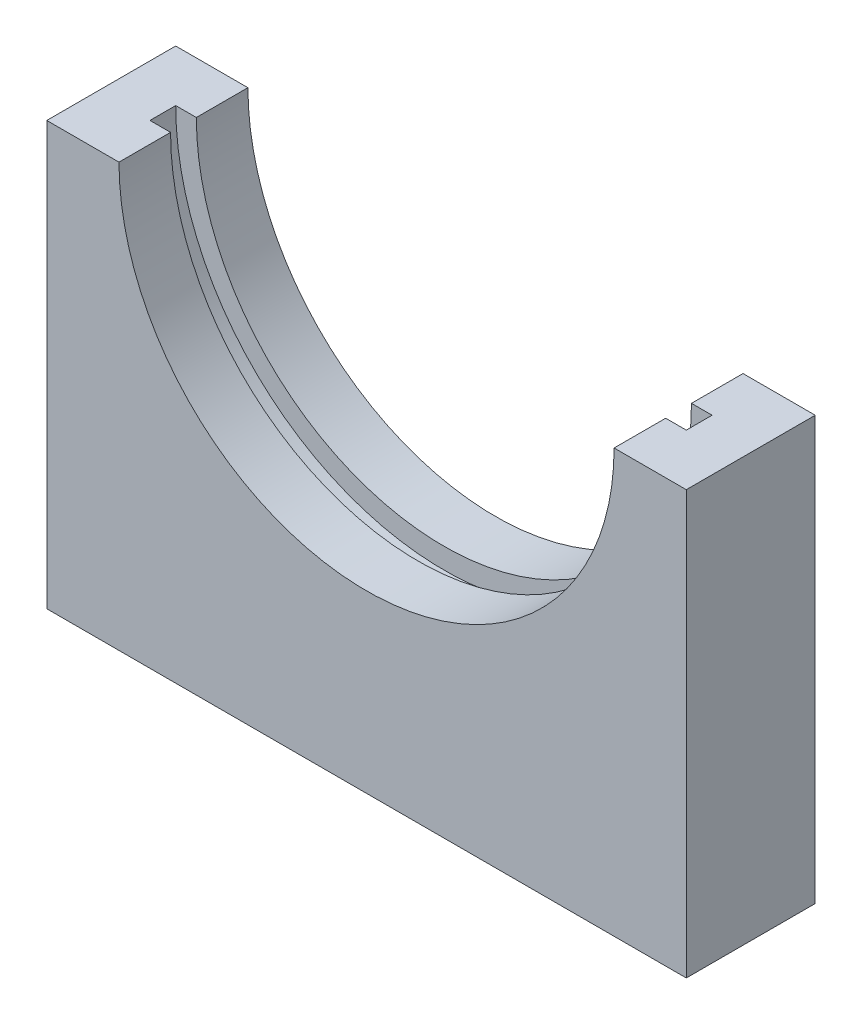
SolidWorks part; units mm, degrees
ref_plane "Front Plane" through (0, 0, 0) normal (0, 0, 1) x (1, 0, 0)
ref_plane "Top Plane" through (0, 0, 0) normal (0, 1, 0) x (1, 0, 0)
ref_plane "Right Plane" through (0, 0, 0) normal (1, 0, 0) x (0, 0, -1)
sketch "Sketch1" plane through (0, 0, 0) normal (0, 0, 1) x (1, 0, 0)
  line L0 (-26, 0) -> (-31, 0)
  line L1 (26, 0) -> (31, 0)
  line L2 (-31, 0) -> (-31, -41)
  line L3 (-31, -41) -> (-31, -23.434)
  line L4 (31, 0) -> (31, -41)
  line L5 (-31, -41) -> (31, -41)
  arc A0 (-26, 0) -> (26, 0) centre (0, 0) ccw
extrude "Boss-Extrude2" add sketch "Sketch1" along normal blind 2.5 contours A0 L0 L2 L5 L4 L1
sketch "Sketch2" plane through (0, 0, 2.5) normal (0, 0, 1) x (1, 0, 0)
  line L0 (-24, 0) -> (-31, 0)
  line L1 (-31, 0) -> (-31, -41)
  line L2 (-31, -41) -> (31, -41)
  line L3 (-31, -41) -> (31, -41) construction
  line L4 (31, 0) -> (31, -41) construction
  line L5 (31, -41) -> (31, 0)
  line L6 (31, 0) -> (24, 0)
  arc A0 (-24, 0) -> (24, 0) centre (0, 0) ccw
extrude "Boss-Extrude3" add sketch "Sketch2" along normal blind 5
sketch "Sketch3" plane through (0, 0, 0) normal (0, 0, -1) x (-1, 0, 0)
  line L0 (-24, 0) -> (-31, 0)
  line L1 (-31, 0) -> (-31, -41)
  line L2 (-31, -41) -> (31, -41)
  line L3 (31, -41) -> (31, 0)
  line L4 (24, 0) -> (31, 0)
  arc A0 (-24, 0) -> (24, 0) centre (0, 0) ccw
extrude "Boss-Extrude4" add sketch "Sketch3" along normal blind 5
sketch "Sketch4" plane through (0, -41, 0) normal (0, -1, 0) x (-1, 0, 0)
  line L0 (24, -7.5) -> (31, -7.5) construction
  line L3 (31, -7.5) -> (-31, -7.5) construction
  line L4 (31, -7.5) -> (31, 5) construction
  circle A0 centre (0, -1.25) radius 2.75
  point P0 (27.5, -7.5)
  point P5 (0, -1.25)
  dimension "D1" = 6.25
  dimension "D2" = 31
extrude "Cut-Extrude1" cut sketch "Sketch4" against normal blind 10
